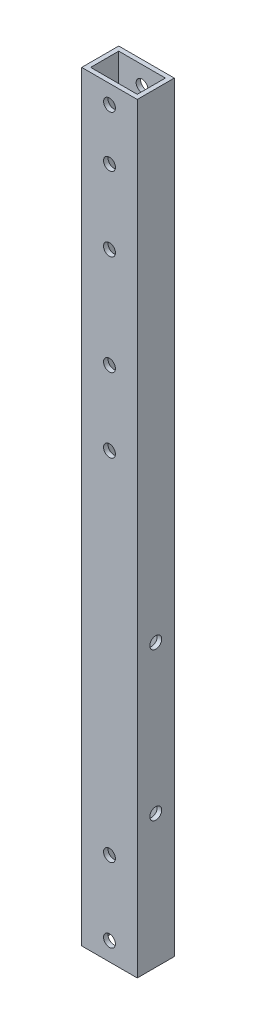
SolidWorks part; units mm, degrees
ref_plane "正面" through (0, 0, 0) normal (0, 0, 1) x (1, 0, 0)
ref_plane "平面" through (0, 0, 0) normal (0, 1, 0) x (1, 0, 0)
ref_plane "右側面" through (0, 0, 0) normal (1, 0, 0) x (0, 0, -1)
sketch "ｽｹｯﾁ1" plane through (0, 0, 0) normal (0, 1, 0) x (1, 0, 0)
  line L0 (-6.3, 3.8) -> (6.3, 3.8)
  line L1 (-7.5, 5) -> (7.5, 5)
  line L2 (-7.5, 5) -> (-7.5, -5)
  line L3 (-7.5, -5) -> (7.5, -5)
  line L4 (7.5, 5) -> (7.5, -5)
  line L5 (-7.5, 5) -> (7.5, -5) construction
  line L6 (-7.5, -5) -> (7.5, 5) construction
  line L7 (6.3, 3.8) -> (6.3, -3.8)
  line L8 (-6.3, -3.8) -> (6.3, -3.8)
  line L9 (-6.3, 3.8) -> (-6.3, -3.8)
  point P0 (0, 0)
  dimension "D1" = 15
  dimension "D2" = 10
  dimension "D3" = 1.2
extrude "ﾎﾞｽ - 押し出し1" add sketch "ｽｹｯﾁ1" along normal mid plane 220
sketch "ｽｹｯﾁ2" plane through (0, 0, -5) normal (0, 0, -1) x (-1, 0, 0)
  line L0 (0, -110) -> (0, -85) construction
  line L1 (-7.5, -110) -> (7.5, -110) construction
  circle A0 centre (0, -85) radius 1.6
  circle A1 centre (0, -105) radius 1.6
  dimension "D2" = 3.2
  dimension "D3" = 3.2
  dimension "D1" = 25
  dimension "D4" = 20
extrude "ｶｯﾄ - 押し出し1" cut sketch "ｽｹｯﾁ2" against normal blind 100
sketch "ｽｹｯﾁ3" plane through (7.5, 0, 0) normal (1, 0, 0) x (0, 0, -1)
  line L1 (0, -110) -> (0, 0) construction
  line L2 (-5, -110) -> (5, -110) construction
  line L4 (6.7084, -36.5) -> (31.7068, -36.5)
  line L5 (31.7068, -36.5) -> (31.7068, -31.5)
  line L6 (31.7068, -31.5) -> (6.7084, -31.5)
  line L7 (6.7084, -31.5) -> (6.7084, -36.5)
  line L8 (6.7084, -36.5) -> (31.7068, -36.5) construction
  line L10 (31.7068, -31.5) -> (6.7084, -31.5) construction
  line L11 (6.7084, -31.5) -> (6.7084, -36.5) construction
  line L12 (6.7084, -76.5) -> (31.7068, -76.5)
  line L13 (31.7068, -76.5) -> (31.7068, -71.5)
  line L14 (31.7068, -71.5) -> (6.7084, -71.5)
  line L15 (6.7084, -71.5) -> (6.7084, -76.5)
  line L16 (6.7084, -76.5) -> (31.7068, -76.5) construction
  line L18 (31.7068, -71.5) -> (6.7084, -71.5) construction
  line L19 (6.7084, -71.5) -> (6.7084, -76.5) construction
  line L26 (31.7068, -36.5) -> (31.7068, -31.5)
  line L27 (31.7068, -76.5) -> (31.7068, -71.5)
  circle A0 centre (0, -34) radius 1.6
  circle A1 centre (0, -74) radius 1.6
  dimension "D3" = 3.2
  dimension "D4" = 3.2
  dimension "D5" = 36
  dimension "D6" = 40
  dimension "D1" = 0
  dimension "D2" = 0
extrude "ｶｯﾄ - 押し出し2" cut sketch "ｽｹｯﾁ3" against normal blind 15 contours A0 | A1
sketch "ｽｹｯﾁ5" plane through (0, 110, 0) normal (0, 1, 0) x (1, 0, 0)
  line L4 (7.5, -5) -> (7.5, 5)
  line L5 (7.5, 5) -> (-7.5, 5)
  line L6 (-7.5, 5) -> (-7.5, -5)
  line L7 (-7.5, -5) -> (7.5, -5)
  line L8 (7.5, -5) -> (7.5, 5)
  line L9 (7.5, 5) -> (-7.5, 5)
  line L10 (-7.5, 5) -> (-7.5, -5)
  line L11 (-7.5, -5) -> (7.5, -5)
  dimension "D1" = 0
extrude "ｶｯﾄ - 押し出し4" cut sketch "ｽｹｯﾁ5" against normal blind 14.5
sketch "ｽｹｯﾁ6" plane through (0, 0, -5) normal (0, 0, -1) x (-1, 0, 0)
  line L0 (0, 95.5) -> (0, 90.5) construction
  line L1 (-7.5, 95.5) -> (7.5, 95.5) construction
  line L2 (0, 90.5) -> (0, 76.66) construction
  line L3 (0, 76.66) -> (0, 56.66) construction
  circle A0 centre (0, 90.5) radius 1.6
  circle A1 centre (0, 76.66) radius 1.6
  circle A2 centre (0, 56.66) radius 1.6
  dimension "D2" = 3.2
  dimension "D5" = 3.2
  dimension "D6" = 3.2
  dimension "D1" = 5
  dimension "D3" = 13.84
  dimension "D4" = 20
extrude "ｶｯﾄ - 押し出し5" cut sketch "ｽｹｯﾁ6" against normal blind 15
sketch "ｽｹｯﾁ7" plane through (0, 0, -5) normal (0, 0, -1) x (-1, 0, 0)
  circle A0 centre (0, 9.6) radius 1.6 construction
  circle A1 centre (0, 29.6) radius 1.6 construction
  circle A2 centre (0, 9.6) radius 1.6
  circle A3 centre (0, 29.6) radius 1.6
extrude "ｶｯﾄ - 押し出し6" cut sketch "ｽｹｯﾁ7" against normal blind 10
